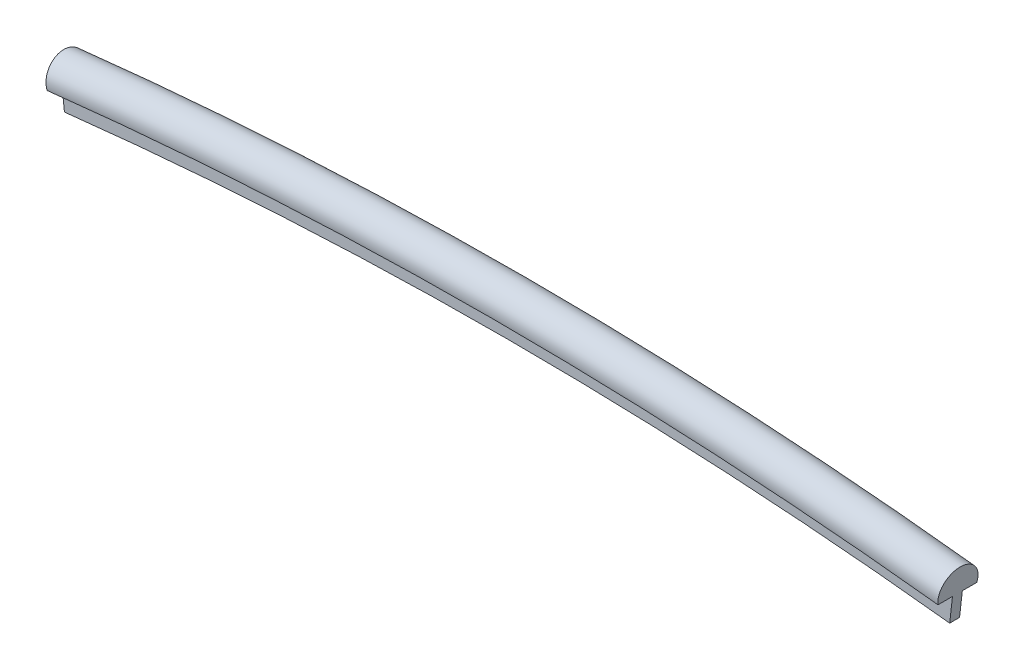
SolidWorks part; units mm, degrees
ref_plane "Front Plane" through (0, 0, 0) normal (0, 0, 1) x (1, 0, 0)
ref_plane "Top Plane" through (0, 0, 0) normal (0, 1, 0) x (1, 0, 0)
ref_plane "Right Plane" through (0, 0, 0) normal (1, 0, 0) x (0, 0, -1)
sketch "Sketch2" plane through (0, 0, 0) normal (1, 0, 0) x (0, 0, -1)
  line L0 (0, 241.3) -> (0, 0) construction
  line L2 (0, 241.3) -> (0, 239.8) construction
  line L3 (0, 239.8) -> (0.3, 239.8)
  line L4 (0, 239.8) -> (-0.3, 239.8)
  line L5 (-0.3, 239.8) -> (-0.3, 241.3)
  line L6 (0.3, 239.8) -> (0.3, 241.3)
  line L7 (0, 241.3) -> (0, 242.8) construction
  line L8 (-1.18, 241.3) -> (-0.3, 241.3)
  line L9 (0.3, 241.3) -> (1.18, 241.3)
  arc A0 (-1.18, 241.3) -> (1.18, 241.3) centre (0, 241.586) cw
  point P14 (0, 241.3)
ref_axis "Axis2" through (0, 0, 70.5976) along (0, 0, -1)
revolve "Revolve1" add sketch "Sketch2" angle 6.447 about axis through (0, 0, 70.5976) along (0, 0, -1)
